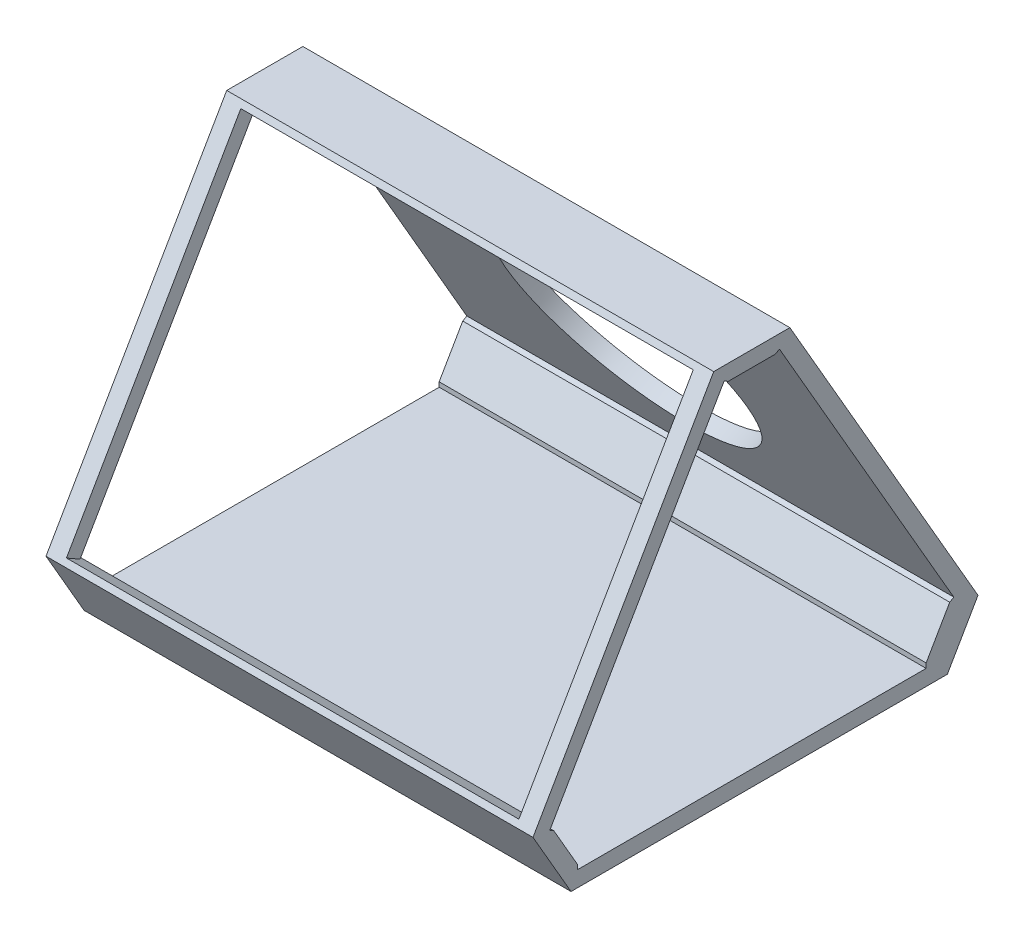
SolidWorks part; units mm, degrees
ref_plane "Front Plane" through (0, 0, 0) normal (0, 0, 1) x (1, 0, 0)
ref_plane "Top Plane" through (0, 0, 0) normal (0, 1, 0) x (1, 0, 0)
ref_plane "Right Plane" through (0, 0, 0) normal (1, 0, 0) x (0, 0, -1)
sketch "Sketch3" plane through (0, 0, 0) normal (1, 0, 0) x (0, 0, -1)
  line L0 (0, 0) -> (141, 0) construction
  line L1 (141, 0) -> (70.5, 122.1096) construction
  line L2 (70.5, 122.1096) -> (0, 0) construction
  line L3 (7.5, 12.9904) -> (15, 0)
  line L4 (7.5, 12.9904) -> (0, 0) construction
  line L5 (0, 0) -> (15, 0) construction
  line L6 (15, 0) -> (15, -1.5)
  line L7 (15, -1.5) -> (126, -1.5)
  line L8 (70.5, 122.1096) -> (70.5, 0) construction
  line L9 (133.5, 12.9904) -> (126, 0)
  line L10 (126, -1.5) -> (126, 0)
  line L11 (7.5, 12.9904) -> (6.201, 13.7404)
  line L12 (6.201, 13.7404) -> (61.701, 109.8692)
  line L13 (61.701, 109.8692) -> (63, 109.1192)
  line L14 (63, 109.1192) -> (78, 109.1192)
  line L15 (79.299, 109.8692) -> (134.799, 13.7404)
  line L16 (134.799, 13.7404) -> (133.5, 12.9904)
  line L17 (78, 109.1192) -> (79.299, 109.8692)
  line L18 (58.3812, 114.1192) -> (0.8605, 14.4904)
  line L19 (0.8605, 14.4904) -> (12.9793, -6.5)
  line L20 (12.9793, -6.5) -> (132.75, -6.5)
  line L21 (132.75, -6.5) -> (142.5042, 10.3947)
  line L22 (142.5042, 10.3947) -> (82.6188, 114.1192)
  line L23 (82.6188, 114.1192) -> (58.3812, 114.1192)
  line L24 (129.75, 6.4952) -> (137.6271, 1.9474) construction
  line L25 (70.5, -1.5) -> (70.5, -6.5) construction
  line L26 (78, 109.1192) -> (78, 114.1192) construction
  dimension "D1" = 141
  dimension "D2" = 1.5
  dimension "D3" = 111
  dimension "D4" = 15
  dimension "D5" = 5
  dimension "D6" = 5
  dimension "D7" = 5
  dimension "D8" = 5
  dimension "D9" = 5
  dimension "D10" = 9.0957
extrude "Boss-Extrude1" add sketch "Sketch3" along normal blind 155
sketch "Sketch4" plane through (0, 3.25, 5.6292) normal (0, 0.5, 0.866) x (1, 0, 0)
  line L0 (155, 126) -> (0, 126) construction
  line L1 (5.5, 126) -> (149.5, 126)
  line L2 (5.5, 126) -> (5.5, 15)
  line L3 (5.5, 15) -> (149.5, 15)
  line L4 (149.5, 126) -> (149.5, 15)
  line L5 (155, 15) -> (0, 15) construction
  line L6 (5.5, 70.5) -> (0, 70.5) construction
  line L7 (0, 128.0207) -> (0, 12.9793) construction
  line L8 (149.5, 70.5) -> (155, 70.5) construction
  line L9 (155, 128.0207) -> (155, 12.9793) construction
  dimension "D1" = 144
extrude "Cut-Extrude1" cut sketch "Sketch4" against normal up to surface (5 mm away) up to face at (77.5, 61.8048, -33.951)
sketch "Sketch5" plane through (0, 64.3048, -111.3792) normal (0, 0.5, -0.866) x (-1, 0, 0)
  line L0 (-155, -62.25) -> (-77.5, -2.3646) construction
  line L1 (-77.5, -2.3646) -> (-155, 57.5207) construction
  line L2 (0, 57.5207) -> (-77.5, -2.3646) construction
  line L3 (-77.5, -2.3646) -> (0, -62.25) construction
  circle A0 centre (-77.5, -2.3646) radius 38.5
  dimension "D1" = 77
extrude "Cut-Extrude2" cut sketch "Sketch5" against normal blind 10
